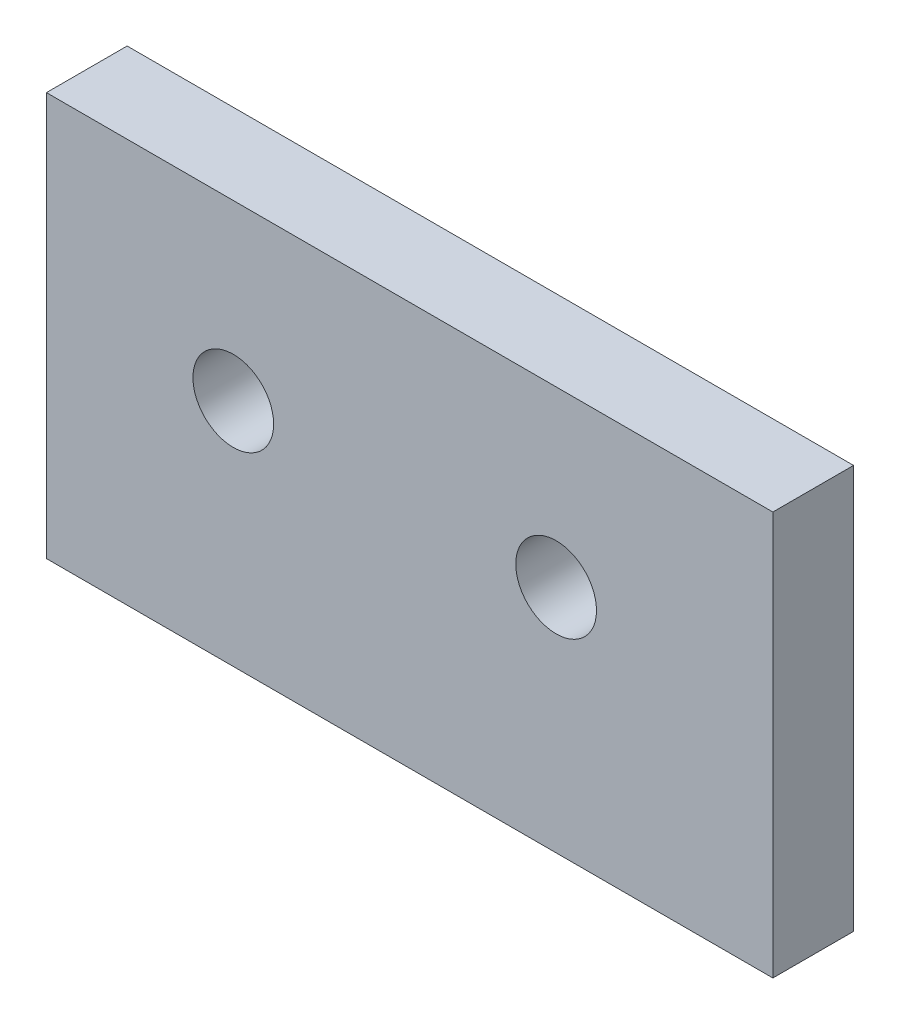
SolidWorks part; units mm, degrees
ref_plane "Płaszczyzna przednia" through (0, 0, 0) normal (0, 0, 1) x (1, 0, 0)
ref_plane "Płaszczyzna górna" through (0, 0, 0) normal (0, 1, 0) x (1, 0, 0)
ref_plane "Płaszczyzna prawa" through (0, 0, 0) normal (1, 0, 0) x (0, 0, -1)
sketch "Szkic1" plane through (0, 0, 0) normal (0, 0, 1) x (1, 0, 0)
  line L1 (0, 0) -> (90, 0)
  line L2 (0, 0) -> (0, 50)
  line L3 (0, 50) -> (90, 50)
  line L4 (90, 0) -> (90, 50)
  circle A0 centre (23.15, 28.5) radius 5
  circle A1 centre (63.15, 28.5) radius 5
  dimension "D3" = 10
  dimension "D4" = 28.5
  dimension "D5" = 23.15
  dimension "D1" = 90
  dimension "D2" = 50
  dimension "D6" = 2
extrude "Dodanie-wyciągnięcie1" add sketch "Szkic1" along normal blind 10
